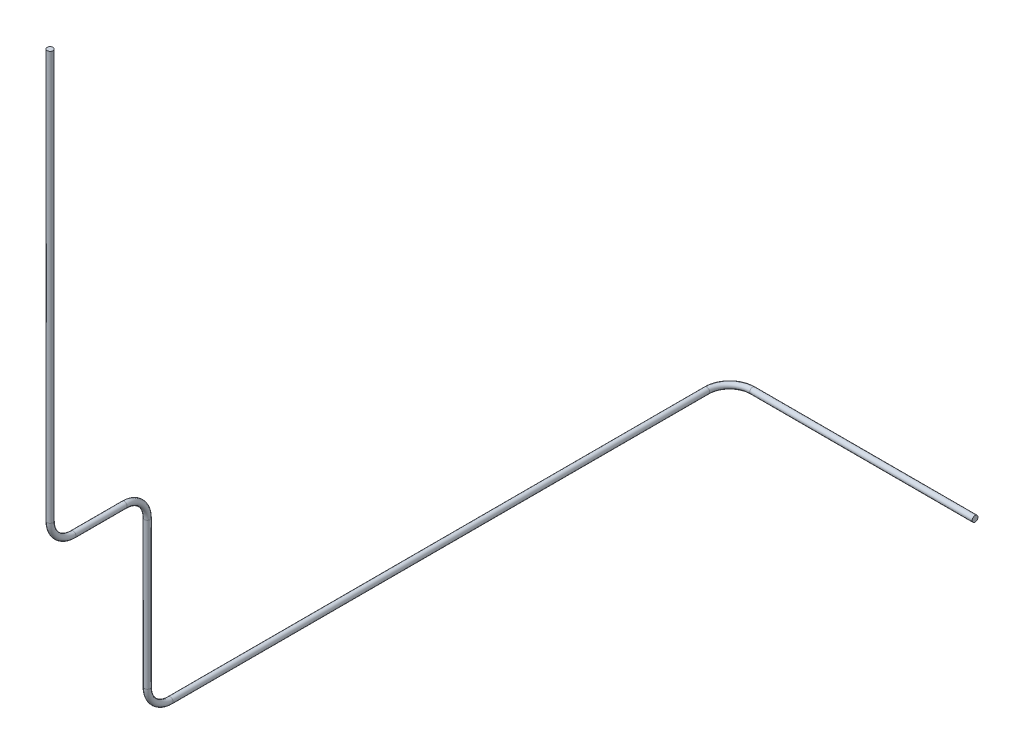
SolidWorks part; units mm, degrees
ref_plane "Alzado" through (0, 0, 0) normal (0, 0, 1) x (1, 0, 0)
ref_plane "Planta" through (0, 0, 0) normal (0, 1, 0) x (1, 0, 0)
ref_plane "Vista lateral" through (0, 0, 0) normal (1, 0, 0) x (0, 0, -1)
sketch3d "Croquis3D1"
  line L2 (-937.242, -1278.8107, 2027.32) -> (-1421.553, -1278.8107, 2027.32)
  line L3 (-1471.553, -1278.8107, 2077.32) -> (-1471.553, -1278.8107, 3245.4874)
  line L4 (-1471.553, -1228.8107, 3295.4874) -> (-1471.553, -910.1907, 3295.4874)
  line L5 (-1471.553, -860.1907, 3345.4874) -> (-1471.553, -860.1907, 3456.883)
  line L6 (-1471.553, -810.1907, 3506.883) -> (-1471.553, 79.7338, 3506.883)
  arc A1 (-1421.553, -1278.8107, 2027.32) -> (-1471.553, -1278.8107, 2077.32) centre (-1421.553, -1278.8107, 2077.32) ccw
  arc A2 (-1471.553, -1278.8107, 3245.4874) -> (-1471.553, -1228.8107, 3295.4874) centre (-1471.553, -1228.8107, 3245.4874) ccw
  arc A3 (-1471.553, -910.1907, 3295.4874) -> (-1471.553, -860.1907, 3345.4874) centre (-1471.553, -910.1907, 3345.4874) ccw
  arc A4 (-1471.553, -860.1907, 3456.883) -> (-1471.553, -810.1907, 3506.883) centre (-1471.553, -810.1907, 3456.883) ccw
  point P4 (-1471.553, -1278.8107, 2027.32)
  point P6 (-1421.553, -1228.8107, 2077.32)
  point P12 (-1471.553, -1278.8107, 2027.32)
  point P13 (-1471.553, -860.1907, 3473.093)
  point P15 (-1471.553, -1278.8107, 3295.4874)
  point P16 (-1521.553, -1228.8107, 3245.4874)
  point P19 (-1471.553, -860.1907, 3295.4874)
  point P20 (-1421.553, -910.1907, 3345.4874)
  point P23 (-1471.553, -860.1907, 3506.883)
  point P24 (-1521.553, -810.1907, 3456.883)
  dimension "D1" = 50
  dimension "D2" = 211.3957
  dimension "D3" = 534.311
sweep "Barrer1" add path "Croquis3D1" circular profile diameter 12.7 parameters "D3"=12.7
